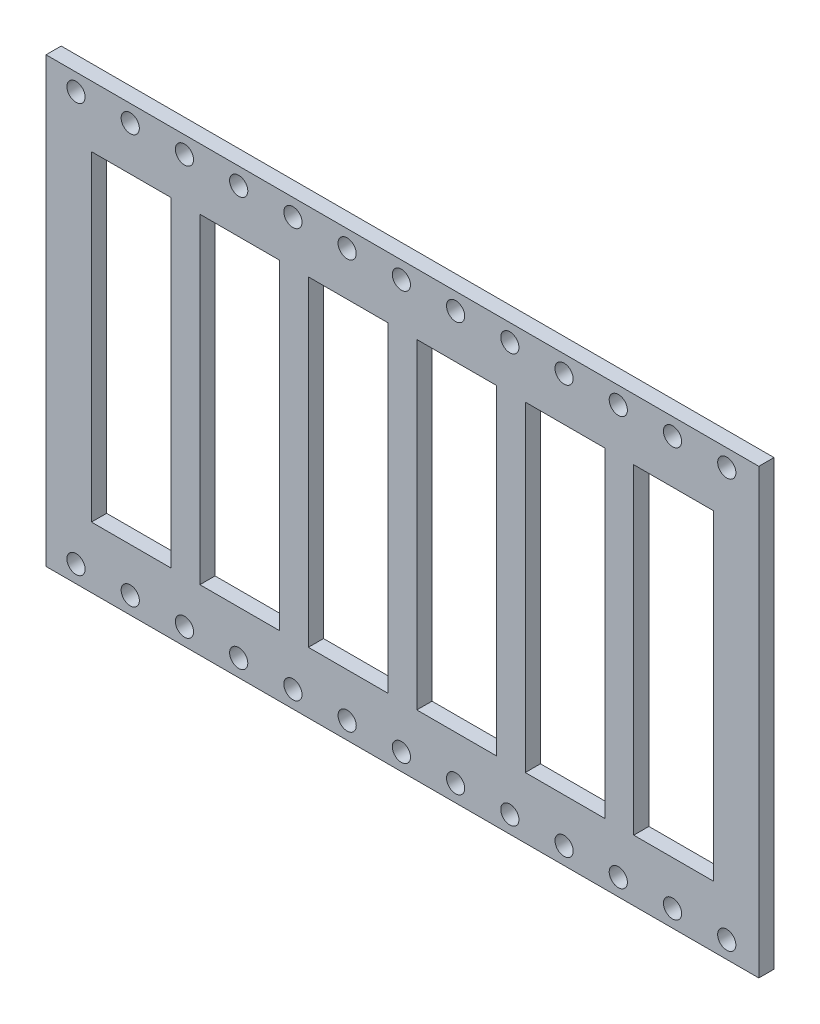
SolidWorks part; units mm, degrees
ref_plane "Front Plane" through (0, 0, 0) normal (0, 0, 1) x (1, 0, 0)
ref_plane "Top Plane" through (0, 0, 0) normal (0, 1, 0) x (1, 0, 0)
ref_plane "Right Plane" through (0, 0, 0) normal (1, 0, 0) x (0, 0, -1)
sketch "Sketch1" plane through (0, 0, 0) normal (0, 0, 1) x (1, 0, 0)
  line L0 (34.25, 211.5) -> (34.25, 251.5) construction
  line L1 (0, 0) -> (426, 0) construction
  line L2 (0, 0) -> (0, 211.5) construction
  line L3 (0, 211.5) -> (426, 211.5) construction
  line L4 (426, 0) -> (426, 211.5) construction
  line L5 (-21.95, -40.32) -> (447.95, -40.32)
  line L6 (0, 211.5) -> (0, 0) construction
  line L7 (105.75, 211.5) -> (105.75, 251.5) construction
  line L8 (8, 211.5) -> (8, 0) construction
  line L9 (447.95, -40.32) -> (447.95, 251.82)
  line L10 (60.5, 211.5) -> (60.5, 0) construction
  line L11 (177.25, 211.5) -> (177.25, 251.5) construction
  line L12 (79.5, 211.5) -> (79.5, 0) construction
  line L13 (8, 211.5) -> (60.5, 211.5)
  line L14 (426, 211.5) -> (426, 0) construction
  line L15 (8, 211.5) -> (8, 0)
  line L16 (418, 211.5) -> (418, 0) construction
  line L17 (132, 211.5) -> (132, 0) construction
  line L18 (8, 0) -> (60.5, 0)
  line L19 (151, 211.5) -> (151, 0) construction
  line L20 (60.5, 211.5) -> (60.5, 0)
  line L21 (203.5, 211.5) -> (203.5, 0) construction
  line L22 (79.5, 0) -> (132, 0)
  line L23 (222.5, 211.5) -> (222.5, 0) construction
  line L24 (79.5, 0) -> (79.5, 211.5)
  line L25 (275, 211.5) -> (275, 0) construction
  line L26 (79.5, 211.5) -> (132, 211.5)
  line L27 (294, 211.5) -> (294, 0) construction
  line L28 (132, 0) -> (132, 211.5)
  line L29 (346.5, 211.5) -> (346.5, 0) construction
  line L30 (151, 211.5) -> (203.5, 211.5)
  line L31 (365.5, 211.5) -> (365.5, 0) construction
  line L32 (151, 211.5) -> (151, 0)
  line L33 (0, 0) -> (426, 0) construction
  line L34 (0, 0) -> (0, -40) construction
  line L35 (0, -40) -> (426, -40) construction
  line L36 (426, 0) -> (426, -40) construction
  line L37 (0, 211.5) -> (426, 211.5) construction
  line L38 (0, 211.5) -> (0, 251.5) construction
  line L39 (0, 251.5) -> (426, 251.5) construction
  line L40 (426, 211.5) -> (426, 251.5) construction
  line L41 (151, 0) -> (203.5, 0)
  line L42 (203.5, 211.5) -> (203.5, 0)
  line L43 (222.5, 0) -> (275, 0)
  line L44 (222.5, 0) -> (222.5, 211.5)
  line L45 (222.5, 211.5) -> (275, 211.5)
  line L46 (275, 0) -> (275, 211.5)
  line L47 (294, 211.5) -> (346.5, 211.5)
  line L48 (294, 211.5) -> (294, 0)
  line L49 (294, 0) -> (346.5, 0)
  line L50 (346.5, 211.5) -> (346.5, 0)
  line L51 (365.5, 0) -> (418, 0)
  line L52 (365.5, 0) -> (365.5, 211.5)
  line L53 (365.5, 211.5) -> (418, 211.5)
  line L54 (418, 0) -> (418, 211.5)
  line L55 (-21.95, -40.32) -> (-21.95, 251.82)
  line L56 (248.75, 211.5) -> (248.75, 251.5) construction
  line L57 (320.25, 211.5) -> (320.25, 251.5) construction
  line L58 (391.75, 211.5) -> (391.75, 251.5) construction
  line L59 (-21.95, 251.82) -> (447.95, 251.82)
  line L60 (-21.95, 240.5465) -> (426, 240.5465) construction
  line L61 (-21.95, -29.0465) -> (426, -29.0465) construction
  line L62 (34.25, 0) -> (34.25, -40) construction
  line L63 (320.25, 0) -> (320.25, -40) construction
  line L64 (105.75, 0) -> (105.75, -40) construction
  line L65 (391.75, 0) -> (391.75, -40) construction
  line L66 (177.25, 0) -> (177.25, -40) construction
  line L67 (89.1985, 211.5) -> (89.1985, 251.82) construction
  line L68 (248.75, 0) -> (248.75, -40) construction
  line L69 (89.1985, 0) -> (89.1985, -40.32) construction
  line L70 (158.3258, 251.82) -> (158.3258, 240.5465) construction
  line L71 (158.3258, -40.32) -> (158.3258, -29.0465) construction
  line L72 (-2.18, 251.82) -> (-2.18, -40.32) construction
  line L73 (8, 65.5312) -> (-21.95, 65.5312) construction
  circle A0 centre (33.57, -29.0465) radius 6
  circle A1 centre (69.32, -29.0465) radius 6
  circle A2 centre (105.07, -29.0465) radius 6
  circle A3 centre (140.82, -29.0465) radius 6
  circle A4 centre (176.57, -29.0465) radius 6
  circle A5 centre (212.32, -29.0465) radius 6
  circle A6 centre (248.07, -29.0465) radius 6
  circle A7 centre (283.82, -29.0465) radius 6
  circle A8 centre (319.57, -29.0465) radius 6
  circle A9 centre (355.32, -29.0465) radius 6
  circle A10 centre (391.07, -29.0465) radius 6
  circle A11 centre (426.82, -29.0465) radius 6
  circle A12 centre (-2.18, 240.5465) radius 6
  circle A14 centre (33.57, 240.5465) radius 6
  circle A16 centre (69.32, 240.5465) radius 6
  circle A18 centre (105.07, 240.5465) radius 6
  circle A20 centre (140.82, 240.5465) radius 6
  circle A22 centre (176.57, 240.5465) radius 6
  circle A23 centre (212.32, 240.5465) radius 6
  circle A24 centre (-2.18, -29.0465) radius 6
  circle A25 centre (248.07, 240.5465) radius 6
  circle A26 centre (283.82, 240.5465) radius 6
  circle A27 centre (319.57, 240.5465) radius 6
  circle A28 centre (355.32, 240.5465) radius 6
  circle A29 centre (391.07, 240.5465) radius 6
  circle A30 centre (426.82, 240.5465) radius 6
  dimension "D2" = 13
  dimension "D1" = 5
extrude "Boss-Extrude1" add sketch "Sketch1" along normal blind 10
sketch "Sketch4" plane through (0, 0, 10) normal (0, 0, -1) x (-1, 0, 0)
  line L0 (-391.07, 251.82) -> (-391.07, -40.32) construction
  line L1 (-447.95, 182.8975) -> (21.95, 182.8975) construction
  line L2 (-319.57, 251.82) -> (-319.57, -40.32) construction
  line L3 (21.95, 25.3975) -> (-447.95, 25.3975) construction
  line L4 (-248.07, 251.82) -> (-248.07, -40.32) construction
  line L5 (-176.57, 251.82) -> (-176.57, -40.32) construction
  line L6 (-105.07, 251.82) -> (-105.07, -40.32) construction
  line L7 (-33.57, 251.82) -> (-33.57, -40.32) construction
  line L8 (-447.95, 130.3975) -> (21.95, 130.3975) construction
  line L9 (21.95, 240.5465) -> (-447.95, 240.5465) construction
  line L10 (21.95, 77.8975) -> (-447.95, 77.8975) construction
  line L11 (21.95, -40.32) -> (-447.95, -40.32) construction
  line L12 (-447.95, 251.82) -> (21.95, 251.82) construction
  line L13 (21.95, 251.82) -> (21.95, -40.32) construction
  line L14 (-447.95, -40.32) -> (-447.95, 251.82) construction
  line L15 (21.95, -29.0465) -> (-447.95, -29.0465) construction
  circle A0 centre (-391.07, 25.3975) radius 1.5
  circle A1 centre (-319.57, 25.3975) radius 1.5
  circle A2 centre (-248.07, 25.3975) radius 1.5
  circle A3 centre (-176.57, 25.3975) radius 1.5
  circle A4 centre (-105.07, 25.3975) radius 1.5
  circle A5 centre (-33.57, 25.3975) radius 1.5
  circle A6 centre (-319.57, 77.8975) radius 1.5
  circle A7 centre (-248.07, 77.8975) radius 1.5
  circle A8 centre (-176.57, 77.8975) radius 1.5
  circle A9 centre (-105.07, 77.8975) radius 1.5
  circle A10 centre (-33.57, 77.8975) radius 1.5
  circle A11 centre (-319.57, 130.3975) radius 1.5
  circle A12 centre (-248.07, 130.3975) radius 1.5
  circle A13 centre (-176.57, 130.3975) radius 1.5
  circle A14 centre (-105.07, 130.3975) radius 1.5
  circle A15 centre (-33.57, 130.3975) radius 1.5
  circle A16 centre (-319.57, 182.8975) radius 1.5
  circle A17 centre (-248.07, 182.8975) radius 1.5
  circle A18 centre (-176.57, 182.8975) radius 1.5
  circle A19 centre (-105.07, 182.8975) radius 1.5
  circle A20 centre (-33.57, 182.8975) radius 1.5
  circle A21 centre (-391.07, 77.8975) radius 1.5
  circle A22 centre (-391.07, 130.3975) radius 1.5
  circle A23 centre (-391.07, 182.8975) radius 1.5
  circle A24 centre (-33.57, 240.5465) radius 6
  circle A25 centre (-105.07, 240.5465) radius 6
  circle A26 centre (-176.57, 240.5465) radius 6
  circle A27 centre (-248.07, 240.5465) radius 6
  circle A28 centre (-319.57, 240.5465) radius 6
  circle A29 centre (-391.07, 240.5465) radius 6
  circle A30 centre (-33.57, -29.0465) radius 6
  circle A31 centre (-105.07, -29.0465) radius 6
  circle A32 centre (-176.57, -29.0465) radius 6
  circle A33 centre (-248.07, -29.0465) radius 6
  circle A34 centre (-319.57, -29.0465) radius 6
  circle A35 centre (-391.07, -29.0465) radius 6
  dimension "D2" = 6
  dimension "D5" = 6
  dimension "D1" = 6
  dimension "D3" = 4
  dimension "D4" = 6
